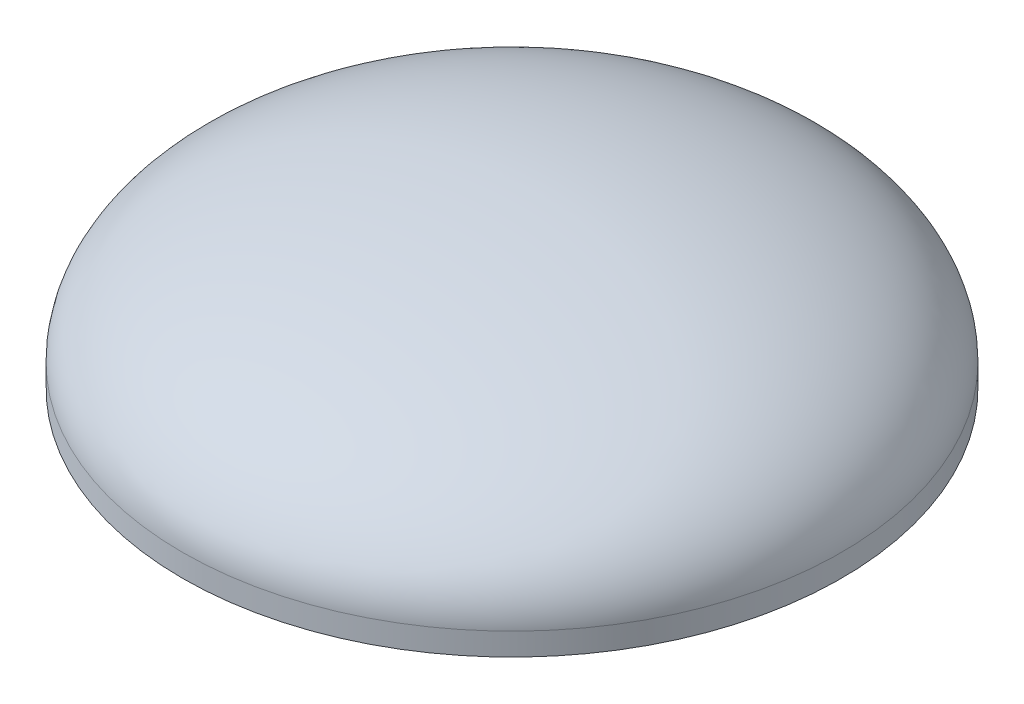
SolidWorks part; units mm, degrees
ref_plane "Front Plane" through (0, 0, 0) normal (0, 0, 1) x (1, 0, 0)
ref_plane "Top Plane" through (0, 0, 0) normal (0, 1, 0) x (1, 0, 0)
ref_plane "Right Plane" through (0, 0, 0) normal (1, 0, 0) x (0, 0, -1)
sketch "Sketch1" plane through (0, 0, 0) normal (0, 1, 0) x (1, 0, 0)
  circle A0 centre (0, 0) radius 0.5
  dimension "D1" = 1
sketch "Sketch2" plane through (0, 0, 0) normal (0, 1, 0) x (1, 0, 0)
  line L0 (0, 0) -> (0, -3.6) construction
  line L1 (0, 0) -> (0, -1.12) construction
  line L2 (-1, -1.12) -> (1, -1.12) construction
  line L3 (0, -3.6) -> (-2.2, -3.6) construction
  line L4 (0, -3.6) -> (2.2, -3.6) construction
  circle A0 centre (-2.2, -3.6) radius 0.65
  circle A1 centre (-1, -1.12) radius 0.375
  circle A2 centre (1, -1.12) radius 0.375
  circle A3 centre (2.2, -3.6) radius 0.65
  point P8 (0, -1.12)
  dimension "D1" = 3.6
  dimension "D5" = 0.75
  dimension "D6" = 1.3
  dimension "D2" = 1.12
  dimension "D3" = 2
  dimension "D4" = 2.2
sketch "Sketch3" plane through (0, 0, 0) normal (0, 1, 0) x (1, 0, 0)
  line L0 (-1.6416, -3.5265) -> (-2.7584, -3.6735)
  line L1 (-0.5, -3.6) -> (0.2484, -3.6) construction
  line L4 (-0.5333, -1.12) -> (-1.4667, -1.12) construction
  line L5 (-1.9887, -2.4018) -> (-2.4113, -4.7982)
  circle A0 centre (-2.2, -3.6) radius 0.1884
  point P11 (-1, -1.12)
  point P14 (-1, -1.12)
  point P16 (1, -1.12)
  point P18 (-2.2, -3.6)
  dimension "D1" = 3.6
  dimension "D2" = 2.2
  dimension "D3" = 7.5
  dimension "D5" = 0.9335
  dimension "D4" = 180
  dimension "D6" = 80
ref_plane "Shuttle-Center-Plane" through (0.4284, 0, 3.254) normal (-0.1305, 0, -0.9914) x (-0.9914, 0, 0.1305)
sketch "Sketch6" plane through (0.4284, 0, 3.254) normal (-0.1305, 0, -0.9914) x (-0.9914, 0, 0.1305)
  line L0 (2.6511, 0) -> (2.6511, 3.1485)
  line L1 (2.6511, 0) -> (2.6511, -2)
  dimension "D1" = 2
sketch "ShuttleBaseLayout" plane through (0.1377, 0, 3.2922) normal (0.1305, 0, 0.9914) x (0.9914, 0, -0.1305)
  line L0 (-2.3579, -0.3457) -> (-2.3579, 2.5883) construction
  line L8 (-2.3579, 0) -> (-4.8788, 0) construction
  line L9 (-4.8788, 0) -> (-6.7695, 0)
  line L10 (-6.7695, 0) -> (-11.4963, 0)
  line L11 (-11.4963, 0) -> (-20.6277, 11.9003)
  line L12 (-20.6277, 11.9003) -> (-17.6527, 14.1832)
  line L13 (-17.6527, 14.1832) -> (-6.7695, 0) construction
  line L14 (-17.6527, 14.1832) -> (-16.4626, 15.0963)
  line L15 (-16.4626, 15.0963) -> (-4.8788, 0)
  line L16 (-14.2052, 15.4397) -> (9.0211, -14.8294) construction
  point P2 (0, 0)
  point P6 (0, 0)
  point P7 (0, 0)
  dimension "D5" = 37.5
  dimension "D6" = 1.5
  dimension "D7" = 15
  dimension "D8" = 3.5
  dimension "D9" = 5.25
sketch "Sketch88" plane through (0.4284, 0, 3.254) normal (-0.1305, 0, -0.9914) x (-0.9914, 0, 0.1305)
  line L0 (36.4179, 32.0963) -> (7.9529, -5) construction
  line L1 (7.9529, -5) -> (9.2133, -5)
  line L2 (9.2133, -5) -> (37.6783, 32.0963)
  line L4 (11.7895, 0) -> (20.9209, 11.9003) construction
  line L5 (7.0627, 0) -> (11.7895, 0) construction
  line L6 (7.9529, -5) -> (20.9209, 11.9003)
  line L7 (20.9209, 11.9003) -> (21.236, 11.9003) construction
  line L8 (21.236, 11.9003) -> (36.733, 32.0963) construction
  line L9 (36.733, 32.0963) -> (37.6783, 32.0963)
  line L10 (36.733, 32.0963) -> (36.4179, 32.0963)
  line L11 (20.9209, 11.9003) -> (36.4179, 32.0963)
  dimension "D1" = 1
  dimension "D2" = 5
  dimension "D3" = 17
  dimension "D4" = 0.25
ref_plane "TopPlane" through (0, 32.0963, 0) normal (0, 1, 0) x (1, 0, 0)
sketch "Sketch89" plane through (0, 32.0963, 0) normal (0, 1, 0) x (1, 0, 0)
  line L0 (-2.2, -3.6) -> (-36.9276, -8.172) construction
  line L1 (-6.772, 31.1276) -> (2.372, -38.3276) construction
  line L2 (-6.772, 31.1276) -> (-2.4096, 31.7019) construction
  line L3 (2.372, -38.3276) -> (6.7343, -37.7533) construction
  line L4 (-2.4096, 31.7019) -> (6.7343, -37.7533) construction
  line L5 (2.1624, -3.0257) -> (-2.2, -3.6) construction
  line L6 (3.428, -29.4942) -> (4.5532, -38.0404) construction
  line L7 (-3.4657, 22.8685) -> (-4.5908, 31.4147) construction
  arc A0 (-6.772, 31.1276) -> (2.372, -38.3276) centre (-2.2, -3.6) ccw construction
  arc A1 (-2.4096, 31.7019) -> (6.7343, -37.7533) centre (2.1624, -3.0257) cw construction
  circle A2 centre (-0.0188, -3.3128) radius 20
  circle A3 centre (3.428, -29.4942) radius 0.836 construction
  circle A4 centre (-3.4657, 22.8685) radius 0.836 construction
  circle A5 centre (-0.0188, -3.3128) radius 22
  point P0 (-2.2, -3.6)
  point P7 (-36.9276, -8.172)
  point P20 (0, 0)
  dimension "D2" = 40
  dimension "D3" = 1.672
  dimension "D5" = 44
  dimension "D1" = 4.4
  dimension "D4" = 8.62
extrude "Boss-Extrude1" add sketch "Sketch89" along normal blind 1.5
sketch "Sketch91" plane through (0.4284, 0, 3.254) normal (-0.1305, 0, -0.9914) x (-0.9914, 0, 0.1305)
  line L0 (0.4511, 46.3612) -> (0.4511, 8.7873) construction
sketch "Sketch92" plane through (0.4284, 0, 3.254) normal (-0.1305, 0, -0.9914) x (-0.9914, 0, 0.1305)
  line L0 (0.4511, 33.5963) -> (20.4511, 33.5963) construction
  line L1 (0.4511, 41.5963) -> (0.4511, 33.5963) construction
  line L2 (0.4511, 200046.3612) -> (0.4511, -199991.2127) construction
  line L3 (0.4511, 41.5963) -> (0.4511, 43.0963)
  line L4 (22.4511, 33.5963) -> (20.4511, 33.5963)
  ellipse E0 centre (0.4511, 33.5963) end of major axis (-19.5489, 33.5963) minor radius 8 (0.4511, 41.5963) -> (20.4511, 33.5963) cw
  ellipse E1 centre (0.4511, 33.5963) end of major axis (-21.5489, 33.5963) minor radius 9.5 (0.4511, 43.0963) -> (22.4511, 33.5963) cw
  dimension "D1" = 8
  dimension "D2" = 1.5
revolve "Revolve1" add sketch "Sketch92" angle 360 about L0
equation "\"DriveAngle\"= 37.5"
equation "\"ThreadedRodOffset\"=1.5"
equation "\"ShuttleOffsetCenter\"= 3.5mm"
equation "\"RotationalCenterAP\"=3.6"
equation "\"D1@Sketch3\"=\"RotationalCenterAP\""
equation "\"RotationalCenterML\"= 2.2"
equation "\"D2@Sketch3\"=\"RotationalCenterML\""
equation "\"BaseRotationAngle\"= \"RotationalSpacing\" / 2"
equation "\"D3@Sketch3\"=\"BaseRotationAngle\""
equation "\"HolderBottomDistanceAboveProjection\"= 5mm"
equation "\"HolderHeight\"=1.5"
equation "\"CannulaOffset\"= 2"
equation "\"D1@Sketch6\"=\"CannulaOffset\""
equation "\"BaseWidening\"=0.5"
equation "\"TetrodeCanulaDiameter\"= 1.3mm"
equation "\"D6@Sketch2\"=\"TetrodeCanulaDiameter\""
equation "\"StimElectrodeCanulaDiameter\"= 0.75mm"
equation "\"D5@Sketch2\"=\"StimElectrodeCanulaDiameter\""
equation "\"TapDrill0_80\"=1.19063"
equation "\"LooseTapDrill0_80\"=1.52"
equation "\"StabilizerRodHole\"=0.8128"
equation "\"RetainingSlotWidth\"=0.5"
equation "\"DriveToEIBSpace\"= 9"
equation "\"0_80_TravelDistance\"=15"
equation "\"D6@ShuttleBaseLayout\" = \"ThreadedRodOffset\""
equation "\"D7@ShuttleBaseLayout\" = \"0_80_TravelDistance\""
equation "\"D5@ShuttleBaseLayout\" = \"DriveAngle\""
equation "\"D8@ShuttleBaseLayout\" = \"ShuttleOffsetCenter\""
equation "\"StabilizerTo0_80Distance\"=2.5"
equation "\"30gaTubingSupport\"=3.5"
equation "\"23GaChannel\"=1.25"
equation "\"RotationalSpacing\"= 15"
equation "\"HalfNumberOfShuttles\"= 4"
equation "\"WeightReductionCutCenter\"= 80"
equation "\"D6@Sketch3\"=\"WeightReductionCutCenter\""
equation "\"EIB-Height\"= 15"
equation "\"19gaLength\"=7.5"
equation "\"ConeThickness\"= 1"
equation "\"D1@Sketch88\"=\"ConeThickness\""
equation "\"ConeBelowBase\"=5"
equation "\"D2@Sketch88\"=\"ConeBelowBase\""
equation "\"ConeAboveRim\" = 17"
equation "\"D3@Sketch88\"=\"ConeAboveRim\""
equation "\"ConeMountAboveBottomRim\"=3"
equation "\"ConeThicknessReduction\"= 0.25"
equation "\"D4@Sketch88\"=\"ConeThicknessReduction\""
equation "\"ConeHeightBlockReduction\"= 3"
equation "\"Rim\"=10"
equation "\"RimHeight\"=2.5"
equation "\"RimHeightLessOffset\"=2.5"
equation "\"D3@Sketch89\"=\"LooseTapDrill0_80\"*1.1"
